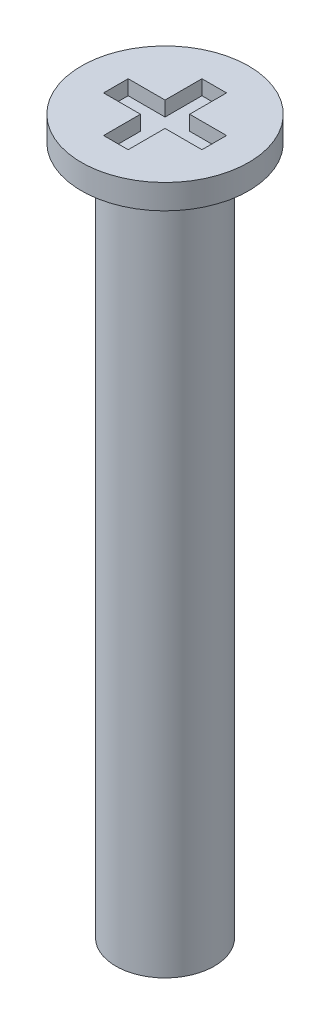
SolidWorks part; units mm, degrees
material "S45C"
ref_plane "正面" through (0, 0, 0) normal (0, 0, 1) x (1, 0, 0)
ref_plane "平面" through (0, 0, 0) normal (0, 1, 0) x (1, 0, 0)
ref_plane "右側面" through (0, 0, 0) normal (1, 0, 0) x (0, 0, -1)
sketch "ｽｹｯﾁ1" plane through (0, 0, 0) normal (0, 0, 1) x (1, 0, 0)
  line L0 (0, 0) -> (1.7, 0)
  line L1 (1.7, 0) -> (1.7, -0.5)
  line L2 (1.7, -0.5) -> (1, -0.5)
  line L3 (1, -0.5) -> (1, -14.5)
  line L4 (1, -14.5) -> (0, -14.5)
  line L5 (0, -14.5) -> (0, 0)
  dimension "D1" = 1.7
  dimension "D2" = 0.5
  dimension "D3" = 1
  dimension "D4" = 14
revolve "回転1" add sketch "ｽｹｯﾁ1" angle 360 about L5
sketch "ｽｹｯﾁ2" plane through (0, 0, 0) normal (0, 1, 0) x (1, 0, 0)
  line L1 (-0.25, 0) -> (0.25, 0)
  line L2 (-0.25, 0) -> (-0.25, 1)
  line L3 (-0.25, 1) -> (0.25, 1)
  line L4 (0.25, 0) -> (0.25, 1)
  line L5 (-0.25, 0) -> (0.25, 1) construction
  line L6 (-0.25, 1) -> (0.25, 0) construction
  point P4 (0, 0.5)
  dimension "D1" = 0
  dimension "D2" = 0.5
  dimension "D3" = 1
  dimension "D4" = 0
extrude "ｶｯﾄ - 押し出し1" cut sketch "ｽｹｯﾁ2" against normal blind 0.3
pattern_circular "円形ﾊﾟﾀｰﾝ1" count 4 over 360 about axis through (0, 0, 0) along (0, 1, 0) of "ｶｯﾄ - 押し出し1"
